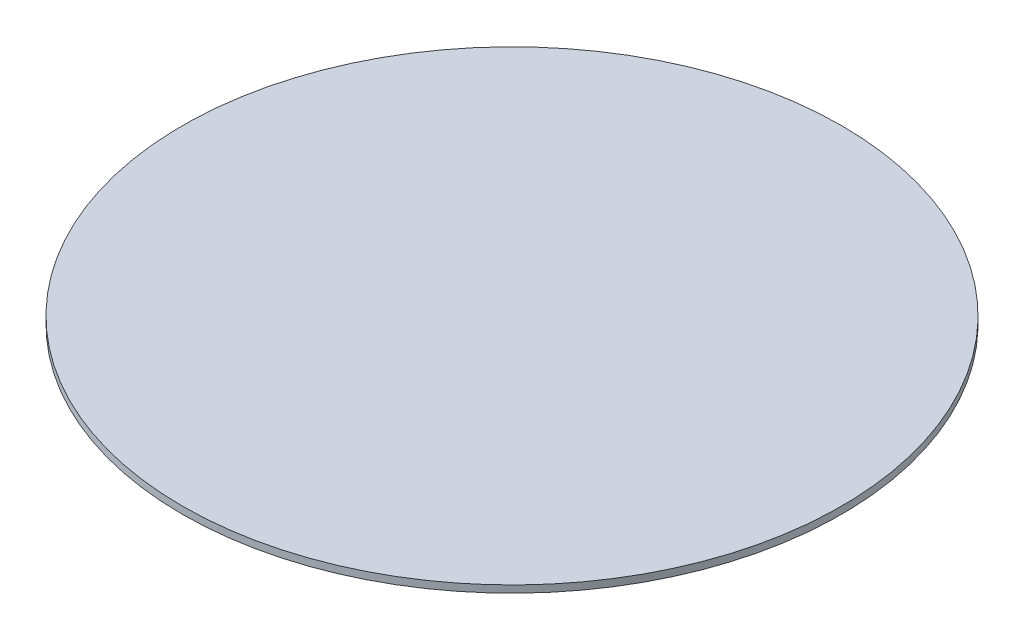
SolidWorks part; units mm, degrees
material "6061-O (SS)"
ref_plane "Front Plane" through (0, 0, 0) normal (0, 0, 1) x (1, 0, 0)
ref_plane "Top Plane" through (0, 0, 0) normal (0, 1, 0) x (1, 0, 0)
ref_plane "Right Plane" through (0, 0, 0) normal (1, 0, 0) x (0, 0, -1)
sketch "Sketch1" plane through (0, 0, 0) normal (0, 1, 0) x (1, 0, 0)
  circle A0 centre (0, 0) radius 150
  point P3 (0, 0)
  dimension "D1" = 300
extrude "Boss-Extrude1" add sketch "Sketch1" along normal blind 3.25
